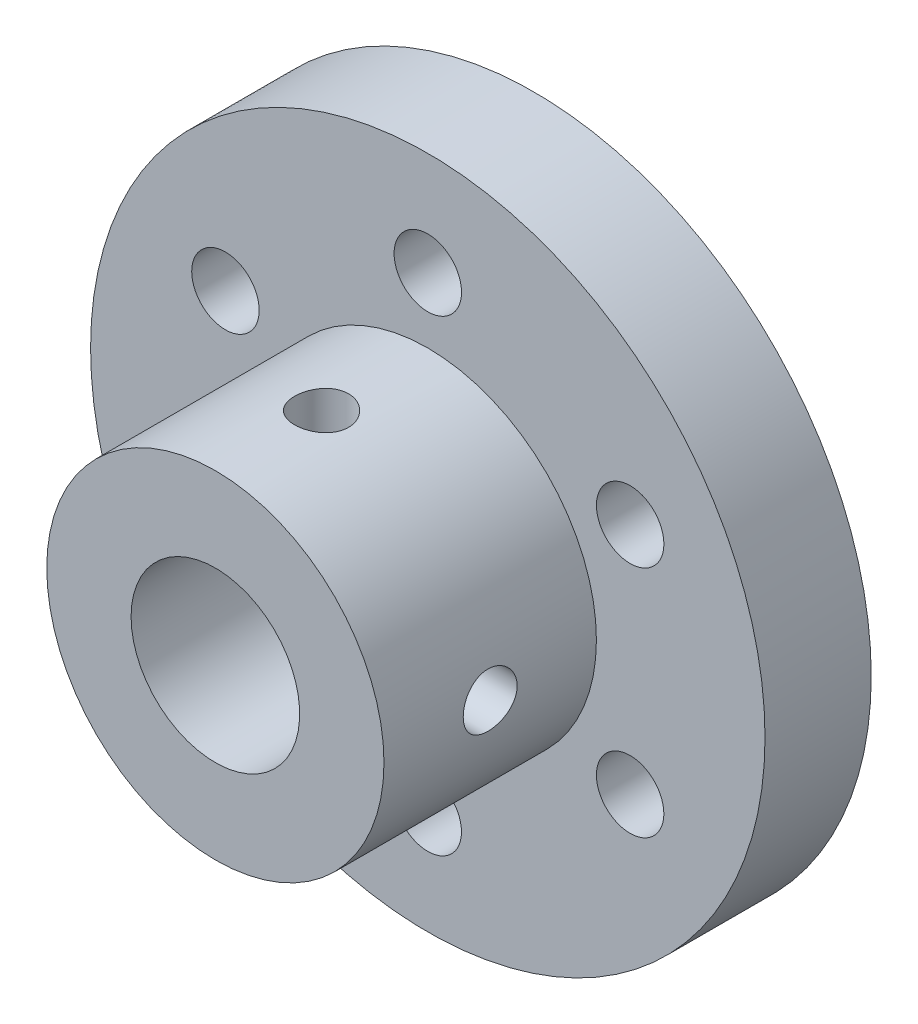
SolidWorks part; units mm, degrees
material "6061-T6 (SS)"
ref_plane "Front Plane" through (0, 0, 0) normal (0, 0, 1) x (1, 0, 0)
ref_plane "Top Plane" through (0, 0, 0) normal (0, 1, 0) x (1, 0, 0)
ref_plane "Right Plane" through (0, 0, 0) normal (1, 0, 0) x (0, 0, -1)
sketch "Sketch1" plane through (0, 0, 0) normal (0, 0, 1) x (1, 0, 0)
  circle A0 centre (0, 0) radius 15.875
  dimension "D1" = 31.75
extrude "Boss-Extrude1" add sketch "Sketch1" along normal blind 15
sketch "Sketch2" plane through (0, 0, 15) normal (0, 0, 1) x (1, 0, 0)
  circle A0 centre (0, 0) radius 7.9375
  circle A1 centre (0, 0) radius 25.3917
  dimension "D1" = 15.875
extrude "Cut-Extrude1" cut sketch "Sketch2" against normal blind 10
sketch "Sketch3" plane through (0, 0, 0) normal (0, 0, -1) x (-1, 0, 0)
  circle A0 centre (0, 0) radius 3.9688
  dimension "D1" = 7.9375
extrude "Cut-Extrude2" cut sketch "Sketch3" against normal through all
sketch "Sketch4" plane through (0, 0, 0) normal (0, 0, -1) x (-1, 0, 0)
  circle A0 centre (0, 0) radius 3.9688
  circle A1 centre (0, 0) radius 4.699
  dimension "D1" = 9.398
extrude "Boss-Extrude2" add sketch "Sketch4" along normal blind 3
sketch "Sketch5" plane through (0, 0, 0) normal (0, 0, -1) x (-1, 0, 0)
  circle A0 centre (0, 0) radius 11 construction
  circle A1 centre (0, 11) radius 1.5875
  circle A2 centre (9.5268, 5.5009) radius 1.5875
  circle A3 centre (9.5278, -5.4991) radius 1.5875
  circle A4 centre (0.002, -11) radius 1.5875
  circle A5 centre (-9.5248, -5.5009) radius 1.5875
  circle A6 centre (-9.5258, 5.4991) radius 1.5875
  circle A13 centre (0, 11) radius 1.5875 [skipped]
  circle A14 centre (9.5268, 5.5009) radius 1.5875 [skipped]
  circle A15 centre (9.5278, -5.4991) radius 1.5875 [skipped]
  circle A16 centre (0.002, -11) radius 1.5875 [skipped]
  circle A17 centre (-9.5248, -5.5009) radius 1.5875 [skipped]
  circle A18 centre (-9.5258, 5.4991) radius 1.5875 [skipped]
  dimension "D1" = 22
  dimension "D2" = 3.175
  dimension "D3" = 6
extrude "Cut-Extrude3" cut sketch "Sketch5" against normal through all
sketch "Sketch6" plane through (0, 0, 0) normal (0, 1, 0) x (1, 0, 0)
  line L0 (-7.9375, -15) -> (7.9375, -15) construction
  circle A0 centre (0, -10) radius 1.27
  dimension "D2" = 2.54
  dimension "D1" = 5
extrude "Cut-Extrude4" cut sketch "Sketch6" along normal through all
sketch "Sketch7" plane through (0, 0, 0) normal (1, 0, 0) x (0, 0, -1)
  line L0 (-15, 7.9375) -> (-15, -7.9375) construction
  circle A0 centre (-10, 0) radius 1.27
  dimension "D1" = 2.54
  dimension "D2" = 5
extrude "Cut-Extrude5" cut sketch "Sketch7" along normal through all
